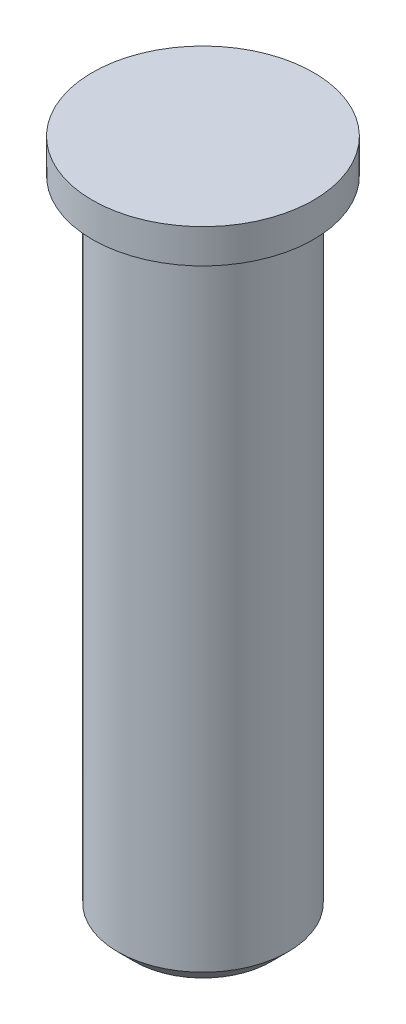
SolidWorks part; units mm, degrees
material "acero"
ref_plane "Alzado" through (0, 0, 0) normal (0, 0, 1) x (1, 0, 0)
ref_plane "Planta" through (0, 0, 0) normal (0, 1, 0) x (1, 0, 0)
ref_plane "Vista lateral" through (0, 0, 0) normal (1, 0, 0) x (0, 0, -1)
sketch "Croquis1" plane through (0, 0, 0) normal (0, 0, 1) x (1, 0, 0)
  line L0 (0, 0) -> (0, -60.9498) construction
  line L1 (0, 0) -> (3.25, 0)
  line L2 (3.25, 0) -> (3.25, -1)
  line L3 (3.25, -1) -> (2.5, -1)
  line L4 (2.5, -1) -> (2.5, -20)
  line L5 (2.5, -20) -> (0, -20)
  line L6 (0, -20) -> (0, 0)
  dimension "D1" = 20
  dimension "D2" = 1
  dimension "D3" = 6.5
  dimension "D4" = 5
revolve "Revolución1" add sketch "Croquis1" angle 360 about L0
chamfer "Chaflán1" distance 0.5 angle 45 1 edges at (0, -20, 2.5)
